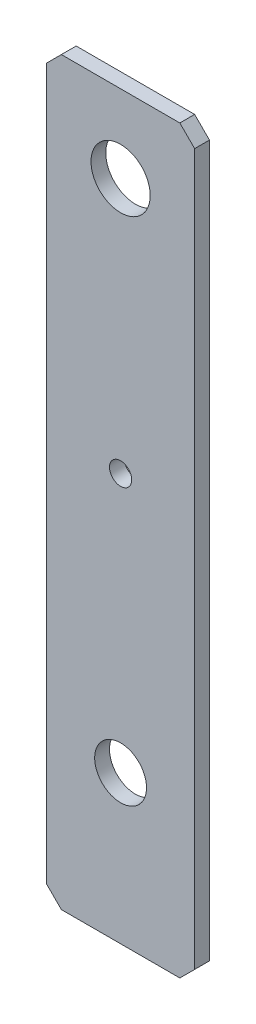
SolidWorks part; units mm, degrees
ref_plane "Front Plane" through (0, 0, 0) normal (0, 0, 1) x (1, 0, 0)
ref_plane "Top Plane" through (0, 0, 0) normal (0, 1, 0) x (1, 0, 0)
ref_plane "Right Plane" through (0, 0, 0) normal (1, 0, 0) x (0, 0, -1)
sketch "Sketch1" plane through (0, 0, 0) normal (0, 0, 1) x (1, 0, 0)
  line L1 (-10, 50) -> (10, 50)
  line L2 (-10, 50) -> (-10, -50)
  line L3 (-10, -50) -> (10, -50)
  line L4 (10, 50) -> (10, -50)
  line L5 (-10, 50) -> (10, -50) construction
  line L6 (-10, -50) -> (10, 50) construction
  point P0 (0, 0)
  dimension "D1" = 100
  dimension "D2" = 20
extrude "Boss-Extrude1" add sketch "Sketch1" along normal blind 2
sketch "Sketch2" plane through (0, 0, 2) normal (0, 0, 1) x (1, 0, 0)
  line L0 (0, 50) -> (0, -50) construction
  line L1 (10, 50) -> (-10, 50) construction
  line L2 (-10, -50) -> (10, -50) construction
  circle A0 centre (0, 39.5) radius 4
  circle A1 centre (0, 5) radius 1.5
  circle A2 centre (0, -30) radius 3.5
  point P12 (0, 39.5)
  dimension "D1" = 7
  dimension "D2" = 8
  dimension "D3" = 3
  dimension "D4" = 20
  dimension "D5" = 55
  dimension "D6" = 10.5
extrude "Cut-Extrude1" cut sketch "Sketch2" against normal up to next
chamfer "Chamfer1" distance 2 angle 45 4 edges at (10, 50, 1) (10, -50, 1) (-10, -50, 1) (-10, 50, 1)
